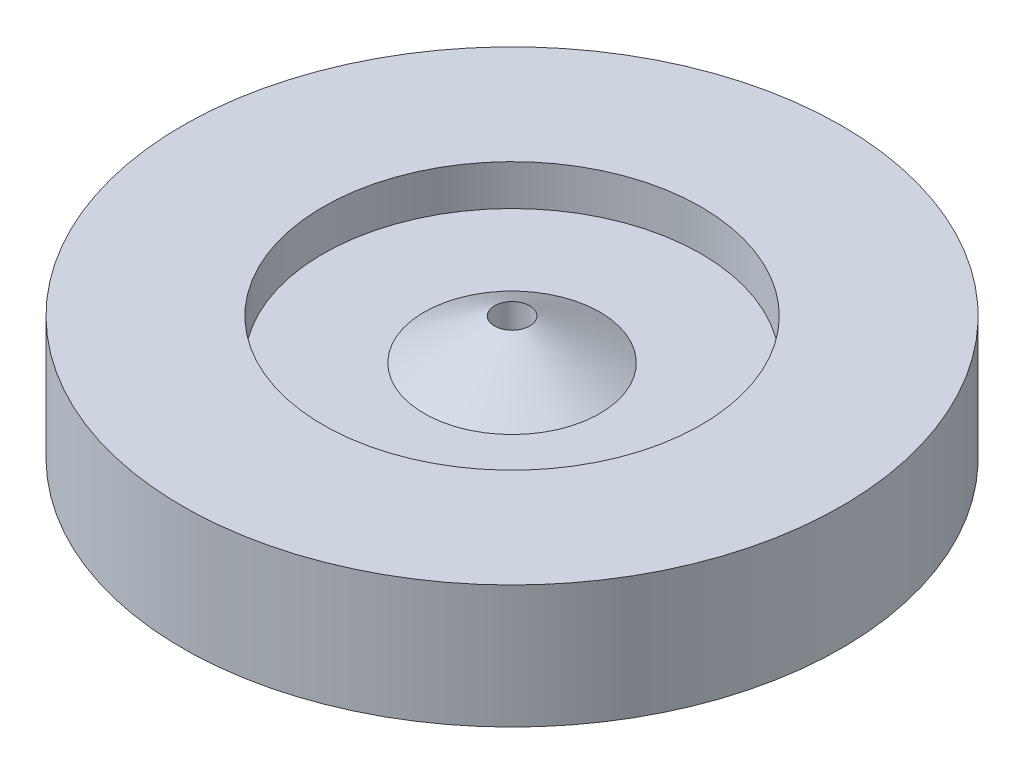
SolidWorks part; units mm, degrees
ref_plane "정면" through (0, 0, 0) normal (0, 0, 1) x (1, 0, 0)
ref_plane "윗면" through (0, 0, 0) normal (0, 1, 0) x (1, 0, 0)
ref_plane "우측면" through (0, 0, 0) normal (1, 0, 0) x (0, 0, -1)
sketch "스케치1" plane through (0, 0, 0) normal (1, 0, 0) x (0, 0, -1)
  line L0 (10, 35) -> (10, -35)
  line L1 (10, 35) -> (50, 11.906)
  line L2 (50, 11.906) -> (107.5, 11.906)
  line L3 (107.5, 11.906) -> (107.5, 35)
  line L4 (107.5, 35) -> (187.5, 35)
  line L5 (187.5, 35) -> (187.5, -35)
  line L6 (55, 0) -> (-55, 0) construction
  line L7 (107.5, -35) -> (187.5, -35)
  line L8 (107.5, -11.906) -> (107.5, -35)
  line L9 (50, -11.906) -> (107.5, -11.906)
  line L10 (10, -35) -> (50, -11.906)
  line L11 (0, 0) -> (0, 92.5333) construction
  point P10 (187.5, 0)
  point P14 (10, 0)
  dimension "D1" = 35
  dimension "D2" = 70
  dimension "D3" = 10
  dimension "D4" = 30
  dimension "D5" = 187.5
  dimension "D6" = 80
  dimension "D7" = 40
revolve "회전1" add sketch "스케치1" angle 360 about L11
